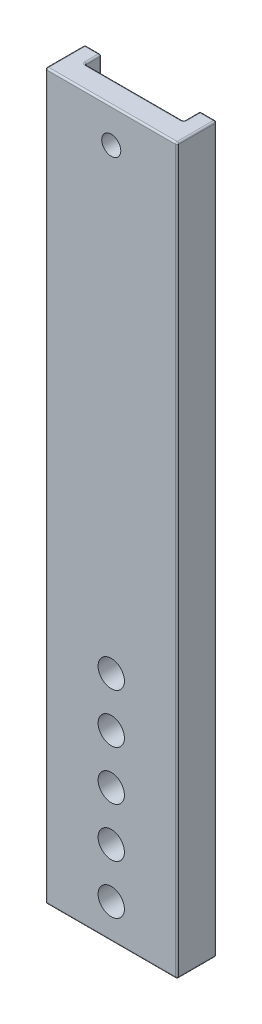
SolidWorks part; units mm, degrees
ref_plane "Alzado" through (0, 0, 0) normal (0, 0, 1) x (1, 0, 0)
ref_plane "Planta" through (0, 0, 0) normal (0, 1, 0) x (1, 0, 0)
ref_plane "Vista lateral" through (0, 0, 0) normal (1, 0, 0) x (0, 0, -1)
sketch "Croquis2" plane through (0, 0, 0) normal (1, 0, 0) x (0, 0, -1)
  line L0 (-24.9488, -14.6462) -> (-12.9488, -14.6462)
  line L15 (-24.9488, -14.6462) -> (-24.9488, 205.3538)
  line L16 (-12.9488, -5.6462) -> (-12.9488, 205.3538)
  line L17 (-24.9488, 205.3538) -> (-12.9488, 205.3538)
  line L18 (-12.9488, -5.6462) -> (-12.9488, -14.6462)
  dimension "D1" = 12
  dimension "D7" = 220
extrude "Saliente-Extruir1" add sketch "Croquis2" along normal blind 40
fillet "Redondeo1" radius 0.5 12 edges at (20, -14.6462, 24.9488) (0, 95.3538, 24.9488) (0, 95.3538, 12.9488) (40, 95.3538, 24.9488) (40, 95.3538, 12.9488) (20, 205.3538, 24.9488) (20, 205.3538, 12.9488) (20, -14.6462, 12.9488) (40, 205.3538, 18.9488) (0, 205.3538, 18.9488) (0, -14.6462, 18.9488) (40, -14.6462, 18.9488)
sketch "Croquis5" plane through (0, 0, 12.9488) normal (0, 0, 1) x (1, 0, 0)
  line L0 (0.5, 204.8538) -> (0.5, -14.1462) construction
  line L5 (0, -14.1462) -> (0.5, -14.1462) construction
  line L6 (0.5, -14.1462) -> (39.5, 204.8538) construction
  line L7 (0.5, 204.8538) -> (35, -14.6462) construction
  line L10 (35, 205.3538) -> (5, 205.3538)
  line L11 (35, 205.3538) -> (35, -14.6462)
  line L12 (35, -14.6462) -> (5, -14.6462)
  line L13 (5, 205.3538) -> (5, -14.6462)
  line L14 (35, 205.3538) -> (5, -14.6462) construction
  line L15 (35, -14.6462) -> (5, 205.3538) construction
  point P4 (0, 0)
  point P6 (37.1312, -14.1462)
  point P7 (20, 95.3538)
  dimension "D1" = 220
  dimension "D2" = 30
extrude "Cortar-Extruir2" cut sketch "Croquis5" along normal blind 5
sketch "Croquis6" plane through (0, 0, 24.9488) normal (0, 0, 1) x (1, 0, 0)
  line L0 (0.5, -14.1462) -> (39.5, -14.1462) construction
  line L1 (39.5, 204.8538) -> (0.5, 204.8538) construction
  line L2 (39.5, -14.1462) -> (39.5, 204.8538) construction
  circle A0 centre (20, -4.1462) radius 4
  circle A3 centre (20, 194.8538) radius 2.9
  circle A6 centre (20, 10.8538) radius 4
  circle A7 centre (20, 25.8538) radius 4
  circle A8 centre (20, 40.8538) radius 4
  circle A9 centre (20, 55.8538) radius 4
  point P12 (0, 0)
  dimension "D1" = 5
  dimension "D2" = 10
  dimension "D3" = 10
  dimension "D4" = 19.5
  dimension "D5" = 19.5
extrude "Cortar-Extruir3" cut sketch "Croquis6" against normal up to next
fillet "Redondeo2" radius 0.5 14 edges at (5, 95.3538, 12.9488) (5, -14.4998, 13.0953) (5, 205.2073, 13.0953) (5, -14.6462, 15.6988) (5, 205.3538, 15.6988) (20, -14.6462, 17.9488) (20, 205.3538, 17.9488) (35, -14.6462, 15.6988) (35, -14.4998, 13.0953) (35, 205.3538, 15.6988) (35, 205.2073, 13.0953) (5, 95.3538, 17.9488) (35, 95.3538, 17.9488) (35, 95.3538, 12.9488)
